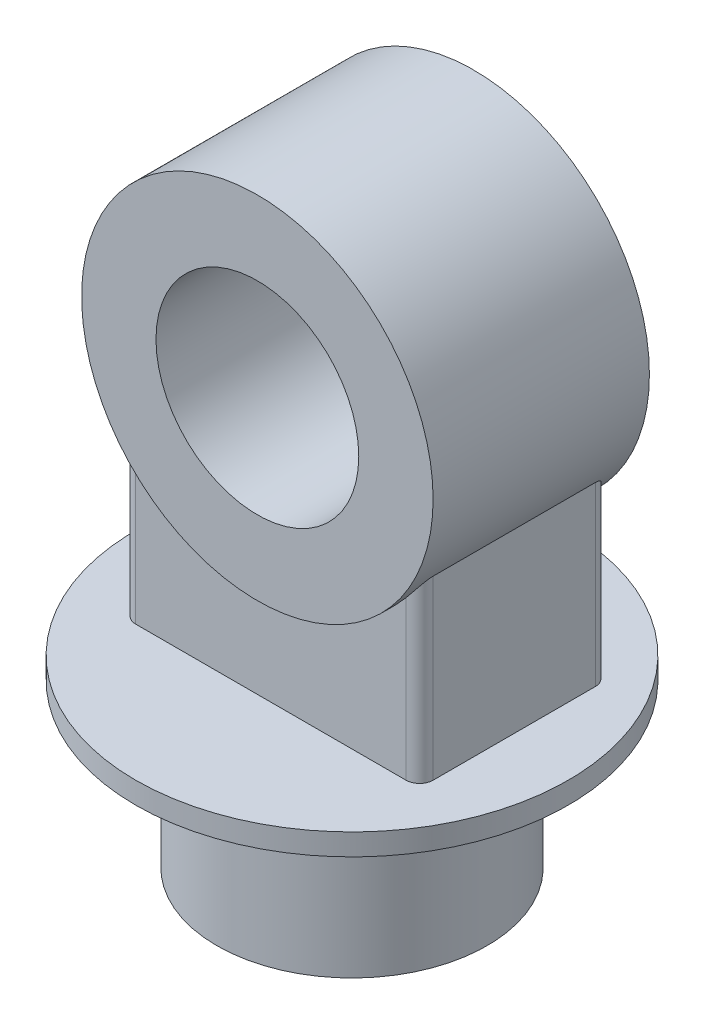
SolidWorks part; units mm, degrees
ref_plane "Ön Düzlem" through (0, 0, 0) normal (0, 0, 1) x (1, 0, 0)
ref_plane "Üst Düzlem" through (0, 0, 0) normal (0, 1, 0) x (1, 0, 0)
ref_plane "Sağ Düzlem" through (0, 0, 0) normal (1, 0, 0) x (0, 0, -1)
sketch "Çizim2" plane through (0, 0, 0) normal (0, 1, 0) x (1, 0, 0)
  circle A0 centre (0, 0) radius 100
  dimension "D1" = 200
extrude "Yükseklik-Ekstrüzyon1" add sketch "Çizim2" along normal blind 120
sketch "Çizim3" plane through (0, 120, 0) normal (0, 1, 0) x (1, 0, 0)
  circle A0 centre (0, 0) radius 160
  dimension "D1" = 320
extrude "Yükseklik-Ekstrüzyon2" add sketch "Çizim3" along normal blind 16
sketch "Çizim4" plane through (0, 0, 0) normal (0, 0, 1) x (1, 0, 0)
  circle A0 centre (0, 336) radius 130
  circle A1 centre (0, 336) radius 75
  dimension "D1" = 260
extrude "Yükseklik-Ekstrüzyon3" add sketch "Çizim4" along normal mid plane 180 separate body
sketch "Çizim6" plane through (0, 136, 0) normal (0, 1, 0) x (1, 0, 0)
  line L0 (107.2777, -60) -> (110, -60)
  line L2 (-110, -60) -> (-110, 80)
  line L3 (-110, 80) -> (110, 80)
  line L4 (110, -60) -> (110, 80)
  line L7 (107.2777, -60) -> (-110, -60)
  point P0 (0, 0)
  dimension "D2" = 220
extrude "Yükseklik-Ekstrüzyon4" add sketch "Çizim6" along normal up to next
sketch "Sketch1" plane through (0, 0, 90) normal (0, 0, 1) x (1, 0, 0)
  circle A0 centre (0, 334.4654) radius 137.3628
  circle A2 centre (0, 334.4654) radius 73.4654
  point P5 (0, 0)
extrude "Cut-Extrude1" cut sketch "Sketch1" against normal blind 20
fillet "Fillet1" radius 10 2 edges at (-110, 201.359, 60) (110, 201.359, 60)
fillet "Fillet2" radius 10 2 edges at (-110, 201.359, -80) (110, 201.359, -80)
